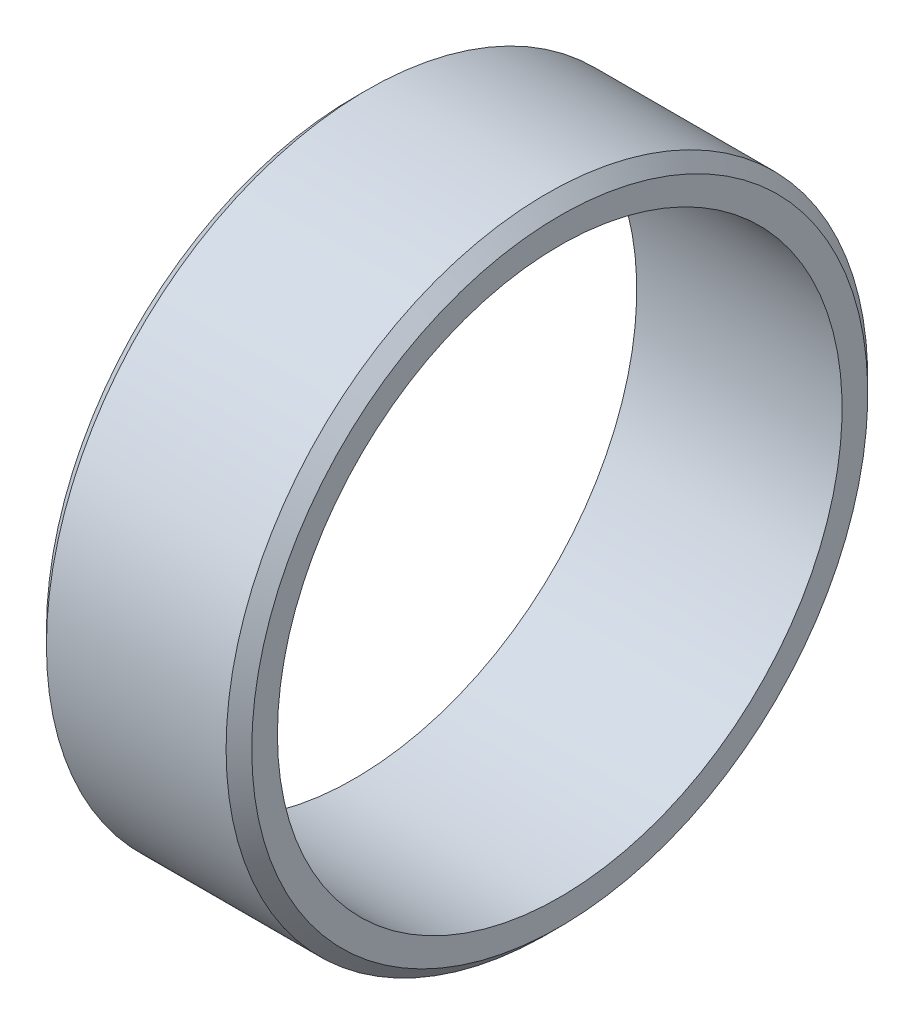
SolidWorks part; units mm, degrees
ref_plane "Plan1" through (0, 0, 0) normal (0, 0, 1) x (1, 0, 0)
ref_plane "Plan2" through (0, 0, 0) normal (0, 1, 0) x (1, 0, 0)
ref_plane "Plan3" through (0, 0, 0) normal (1, 0, 0) x (0, 0, -1)
sketch "Esquisse1" plane through (0, 0, 0) normal (0, 0, 1) x (1, 0, 0)
  line L0 (0, 22) -> (16, 22)
  line L1 (16, 22) -> (16, 24)
  line L2 (16, 24) -> (15, 25)
  line L3 (15, 25) -> (1, 25)
  line L4 (1, 25) -> (0, 24)
  line L5 (0, 24) -> (0, 22)
  line L6 (0, 0) -> (20, 0) construction
  dimension "D1" = 1
  dimension "D2" = 45
  dimension "D3" = 1
  dimension "D4" = 45
  dimension "D5" = 22
  dimension "D6" = 25
  dimension "D7" = 16
revolve "Base-Révolution" add sketch "Esquisse1" angle 360 about L6
